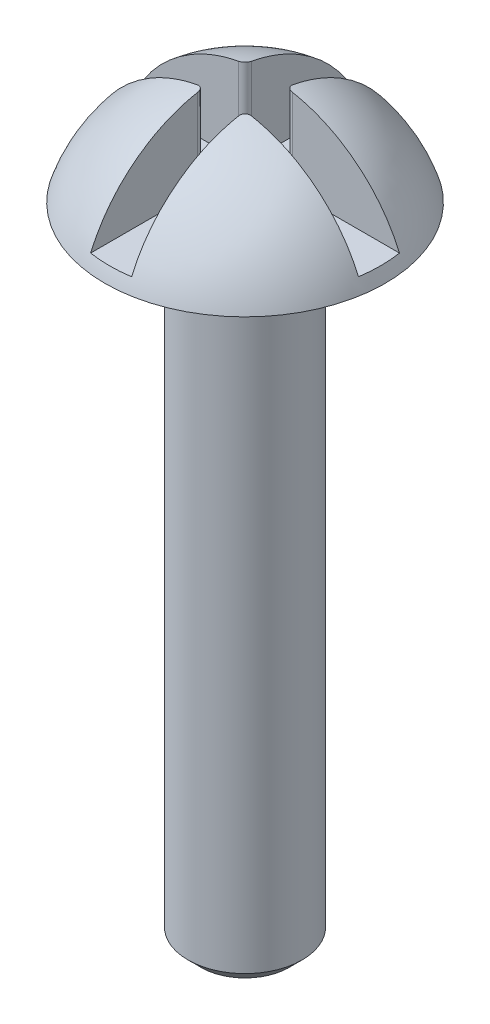
SolidWorks part; units mm, degrees
ref_plane "Front Plane" through (0, 0, 0) normal (0, 0, 1) x (1, 0, 0)
ref_plane "Top Plane" through (0, 0, 0) normal (0, 1, 0) x (1, 0, 0)
ref_plane "Right Plane" through (0, 0, 0) normal (1, 0, 0) x (0, 0, -1)
sketch "Sketch2" plane through (0, 0, 0) normal (1, 0, 0) x (0, 0, -1)
  line L0 (0, 0) -> (2.7813, 0)
  line L1 (0, 0) -> (0, 2.032)
  line L2 (0, 0.4152) -> (0, -1.08) construction
  arc A0 (2.7813, 0) -> (0, 2.032) centre (0, -0.8875) ccw
  dimension "D1" = 2.7813
  dimension "D2" = 2.032
revolve "Head" add sketch "Sketch2" angle 360 about L2
sketch "Sketch3" plane through (0, 0, 0) normal (0, -1, 0) x (1, 0, 0)
  circle A0 centre (0, 0) radius 1.1303
  dimension "D1" = 2.2606
extrude "Shaft" add sketch "Sketch3" along normal blind 12.7
chamfer "Tip" distance 0.254 angle 45 1 edges at (0, -12.7, -1.1303)
sketch "Sketch4" plane through (0, 0, 0) normal (0, 1, 0) x (1, 0, 0)
  line L0 (-0.4064, 0.4064) -> (-0.4064, 2.7813)
  line L1 (-0.4064, -2.7813) -> (0.4064, -2.7813)
  line L2 (-0.4064, -2.7813) -> (-0.4064, -0.4064)
  line L3 (-0.4064, 2.7813) -> (0.4064, 2.7813)
  line L4 (0.4064, -2.7813) -> (0.4064, -0.4064)
  line L5 (-0.4064, -2.7813) -> (0.4064, 2.7813) construction
  line L6 (-0.4064, 2.7813) -> (0.4064, -2.7813) construction
  line L7 (2.7813, -0.4064) -> (0.4064, -0.4064)
  line L8 (2.7813, -0.4064) -> (2.7813, 0.4064)
  line L9 (2.7813, 0.4064) -> (0.4064, 0.4064)
  line L10 (-2.7813, -0.4064) -> (-2.7813, 0.4064)
  line L11 (2.7813, -0.4064) -> (-2.7813, 0.4064) construction
  line L12 (2.7813, 0.4064) -> (-2.7813, -0.4064) construction
  line L13 (-0.4064, -0.4064) -> (-2.7813, -0.4064)
  line L15 (0.4064, 0.4064) -> (0.4064, 2.7813)
  line L17 (-0.4064, 0.4064) -> (-2.7813, 0.4064)
  circle A0 centre (0, 0) radius 2.7813 construction
  point P0 (0, 0)
  point P8 (0, 0)
  dimension "D1" = 0.8128
extrude "Phillips" cut sketch "Sketch4" along normal through all from offset 0.254
fillet "PhillipsFillet" radius 0.127 4 edges at (0.4064, 1.1144, 0.4064) (0.4064, 1.1144, -0.4064) (-0.4064, 1.1144, 0.4064) (-0.4064, 1.1144, -0.4064)
